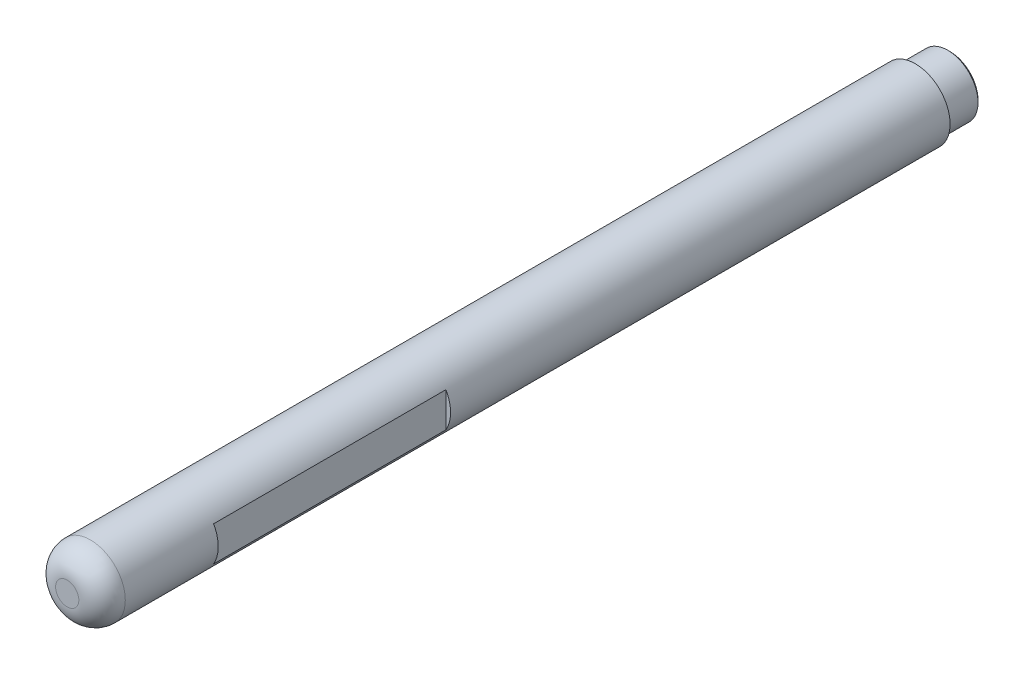
SolidWorks part; units mm, degrees
material "ASTM A36 Aço"
ref_plane "Plano frontal" through (0, 0, 0) normal (0, 0, 1) x (1, 0, 0)
ref_plane "Plano superior" through (0, 0, 0) normal (0, 1, 0) x (1, 0, 0)
ref_plane "Plano direito" through (0, 0, 0) normal (1, 0, 0) x (0, 0, -1)
sketch "Esboço1" plane through (0, 0, 0) normal (0, 0, 1) x (1, 0, 0)
  circle A0 centre (0, 0) radius 7.5
  dimension "D1" = 15
extrude "Ressalto-extrusão1" add sketch "Esboço1" along normal mid plane 190
sketch "Esboço2" plane through (0, 0, -95) normal (0, 0, -1) x (-1, 0, 0)
  circle A2 centre (0, 0) radius 6.5
  circle A3 centre (0, 0) radius 7.5
  circle A4 centre (0, 0) radius 7.5 construction
  dimension "D1" = 13
extrude "Corte-extrusão1" cut sketch "Esboço2" against normal blind 7.5
fillet "Filete1" radius 5 1 edges at (7.5, 0, 95)
hole_wizard "Furo roscado de M6x1.01" positions "Esboço6" profile "Esboço7" tap size "M6x1.0" standard "Ansi Metric"
sketch "Esboço6" plane through (0, 0, -95) normal (0, 0, -1) x (-1, 0, 0)
  point P0 (0, 0)
sketch "Esboço7" plane through (0, 0, -95) normal (1, 0, 0) x (0, 1, 0)
  line L0 (0, 0) -> (0, 17)
  line L1 (0, 17) -> (2.5, 15.4978)
  line L2 (2.5, 15.4978) -> (2.5, 0)
  line L5 (2.5, 0) -> (0, 0)
  line L10 (0, 17) -> (-2.5, 15.4978) construction
  line L11 (0, -6.35) -> (0, 107.95) construction
  dimension "Tap Drill Dia." = 5
  dimension "Tap Drill Depth" = 17
  dimension "Drill Angle" = 118
cosmetic thread "Rosca de furo1" parameters "D1"=12, "D2"=6
chamfer "Chanfro1" distance 0.5 angle 45 1 edges at (-6.5, 0, -95)
sketch "Esboço8" plane through (0, 0, 0) normal (0, 1, 0) x (1, 0, 0)
  line L0 (7.5, -90) -> (7.5, 87.5) construction
  line L1 (7.5, -70) -> (6.5, -70)
  line L2 (7.5, -70) -> (7.5, -20)
  line L3 (7.5, -20) -> (6.5, -20)
  line L4 (6.5, -70) -> (6.5, -20)
  line L5 (-2.5, -95) -> (2.5, -95) construction
  dimension "D1" = 1
  dimension "D2" = 50
  dimension "D3" = 25
extrude "Corte-extrusão2" cut sketch "Esboço8" against normal through all both and the other way through all
